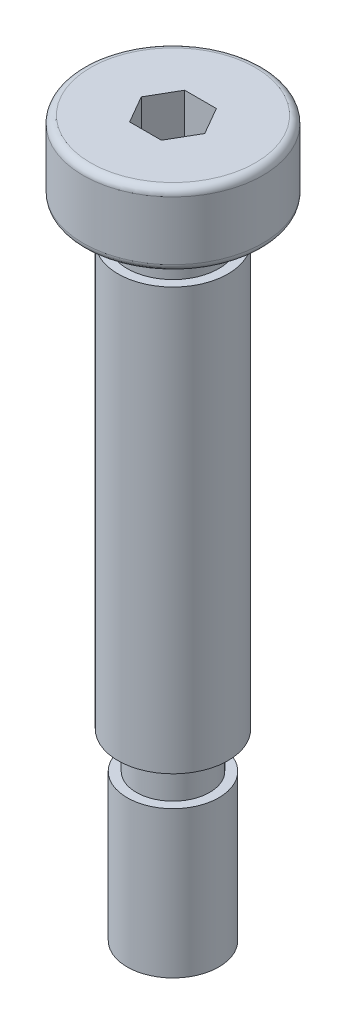
SolidWorks part; units mm, degrees
material "AISI 304"
ref_plane "前视基准面" through (0, 0, 0) normal (0, 0, 1) x (1, 0, 0)
ref_plane "上视基准面" through (0, 0, 0) normal (0, 1, 0) x (1, 0, 0)
ref_plane "右视基准面" through (0, 0, 0) normal (1, 0, 0) x (0, 0, -1)
sketch "草图1" plane through (0, 0, 0) normal (0, 0, 1) x (1, 0, 0)
  line L0 (0, 0) -> (0, 39) construction
  line L1 (0, 39) -> (-4.5, 39)
  line L2 (-4.9, 38.6) -> (-4.9, 35.4)
  line L3 (-4.5, 35) -> (-2.5, 35)
  line L4 (-2.5, 35) -> (-2.5, 33)
  line L5 (-2.5, 33) -> (-3, 33)
  line L6 (-3, 33) -> (-3, 10)
  line L7 (-3, 10) -> (-2, 10)
  line L8 (-2, 10) -> (-2, 8)
  line L9 (-2, 8) -> (-2.5, 8)
  line L10 (-2.5, 8) -> (-2.5, 0)
  line L11 (-2.5, 0) -> (0, 0)
  line L12 (0, 0) -> (0, 39)
  arc A0 (-4.9, 35.4) -> (-4.5, 35) centre (-4.5, 35.4) ccw
  arc A1 (-4.5, 39) -> (-4.9, 38.6) centre (-4.5, 38.6) ccw
  point P17 (-4.9, 35)
  point P20 (-4.9, 39)
  dimension "D11" = 0.4
  dimension "D1" = 4
  dimension "D2" = 9.8
  dimension "D3" = 6
  dimension "D4" = 2
  dimension "D5" = 0.5
  dimension "D6" = 10
  dimension "D7" = 5
  dimension "D8" = 4
  dimension "D9" = 2
  dimension "D10" = 25
revolve "旋转1" add sketch "草图1" angle 360 about L0
cosmetic thread "装饰螺纹线1" parameters "D2"=4.11
sketch "草图2" plane through (0, 39, 0) normal (0, 1, 0) x (1, 0, 0)
  line L1 (0.866, 1.5) -> (-0.866, 1.5)
  line L2 (-0.866, 1.5) -> (-1.7321, 0)
  line L3 (-1.7321, 0) -> (-0.866, -1.5)
  line L4 (-0.866, -1.5) -> (0.866, -1.5)
  line L5 (0.866, -1.5) -> (1.7321, 0)
  line L6 (1.7321, 0) -> (0.866, 1.5)
  circle A0 centre (0, 0) radius 1.5 construction
  dimension "D1" = 3
extrude "切除-拉伸1" cut sketch "草图2" against normal blind 3.5
